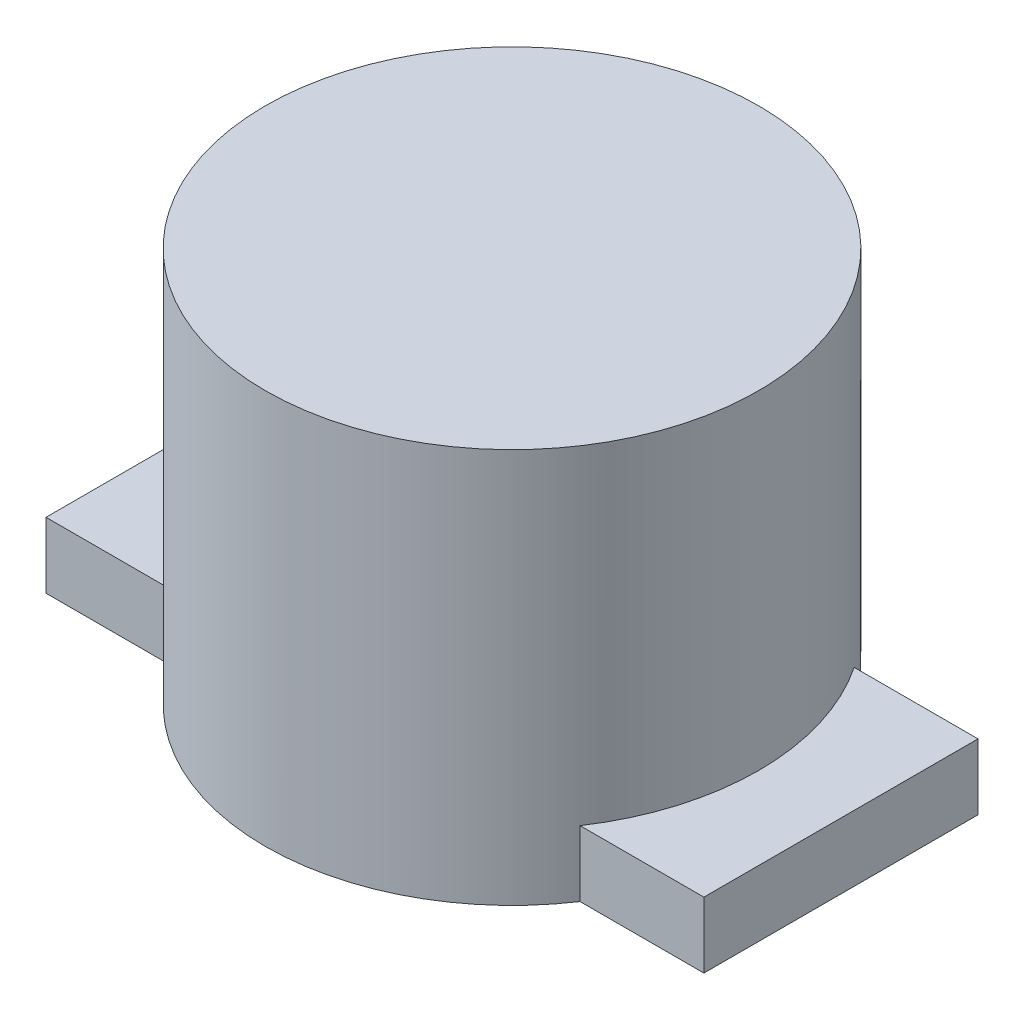
SolidWorks part; units mm, degrees
ref_plane "前视基准面" through (0, 0, 0) normal (0, 0, 1) x (1, 0, 0)
ref_plane "上视基准面" through (0, 0, 0) normal (0, 1, 0) x (1, 0, 0)
ref_plane "右视基准面" through (0, 0, 0) normal (1, 0, 0) x (0, 0, -1)
sketch "草图1" plane through (0, 0, 0) normal (0, 1, 0) x (1, 0, 0)
  line L0 (-12, 0) -> (-9.7417, 0)
  line L2 (0, 0) -> (0, 5)
  line L4 (-12, 0) -> (-12, 5)
  line L5 (-9.7417, 5) -> (-12, 5)
  line L6 (-2.2583, 5) -> (0, 5)
  line L7 (-2.2583, 0) -> (0, 0)
  arc A1 (-2.2583, 5) -> (-9.7417, 5) centre (-6, 2.5) ccw
  arc A2 (-9.7417, 0) -> (-2.2583, 0) centre (-6, 2.5) ccw
extrude "凸台-拉伸1" add sketch "草图1" along normal blind 1.2
sketch "草图2" plane through (0, 1.2, 0) normal (0, 1, 0) x (1, 0, 0)
  circle A0 centre (-6, 2.5) radius 4.5
extrude "凸台-拉伸2" add sketch "草图2" along normal blind 6
